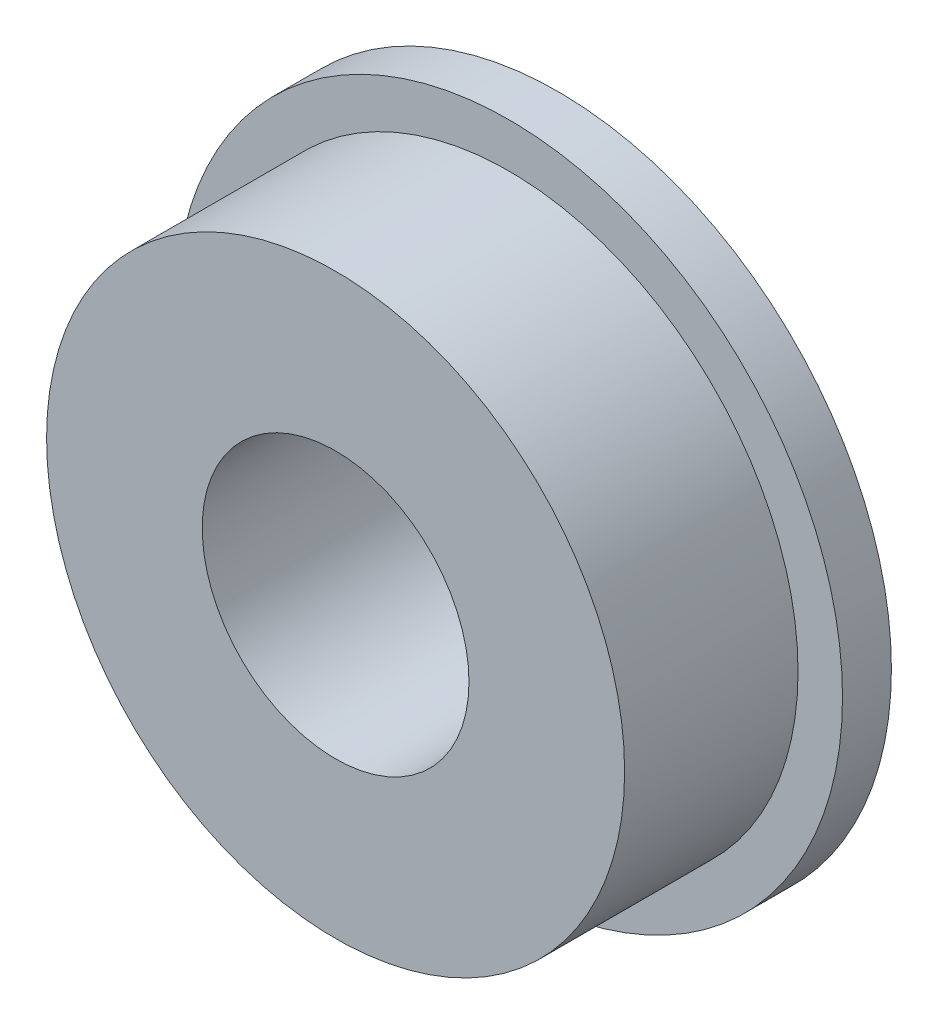
SolidWorks part; units mm, degrees
material "AISI 304"
ref_plane "前视基准面" through (0, 0, 0) normal (0, 0, 1) x (1, 0, 0)
ref_plane "上视基准面" through (0, 0, 0) normal (0, 1, 0) x (1, 0, 0)
ref_plane "右视基准面" through (0, 0, 0) normal (1, 0, 0) x (0, 0, -1)
other "Configuration Table"
sketch "草图1" plane through (0, 0, 0) normal (0, 1, 0) x (1, 0, 0)
  line L0 (0, 0) -> (0, 13.75) construction
  line L1 (3, 0) -> (6.5, 0)
  line L2 (6.5, 0) -> (6.5, 3.9)
  line L3 (6.5, 3.9) -> (7.5, 3.9)
  line L4 (7.5, 3.9) -> (7.5, 5)
  line L5 (7.5, 5) -> (3, 5)
  line L6 (3, 5) -> (3, 0)
  point P8 (6.5, 1.95)
  dimension "D1" = 3
  dimension "D2" = 6.5
  dimension "D3" = 5
  dimension "D4" = 1.1
  dimension "D5" = 7.5
revolve "旋转1" add sketch "草图1" angle 360 about L0
